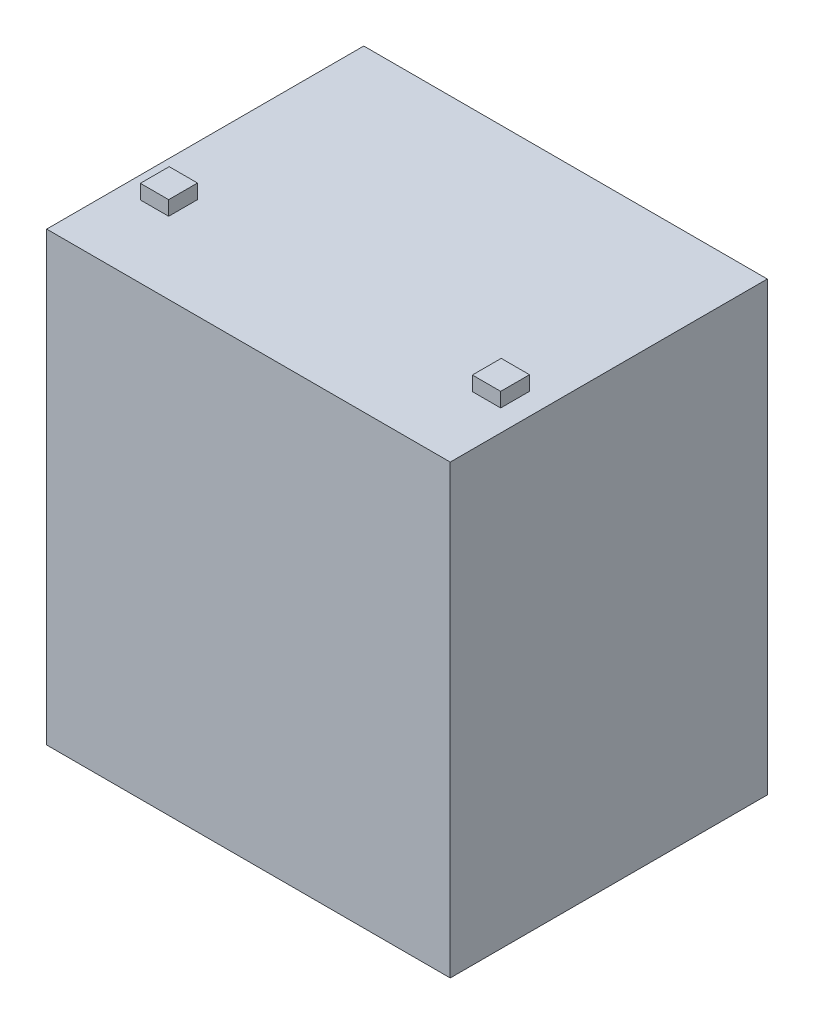
SolidWorks part; units mm, degrees
ref_plane "Front Plane" through (0, 0, 0) normal (0, 0, 1) x (1, 0, 0)
ref_plane "Top Plane" through (0, 0, 0) normal (0, 1, 0) x (1, 0, 0)
ref_plane "Right Plane" through (0, 0, 0) normal (1, 0, 0) x (0, 0, -1)
sketch "Sketch2" plane through (0, 0, 0) normal (0, 0, 1) x (1, 0, 0)
  line L1 (-44.45, -49.2125) -> (44.45, -49.2125)
  line L2 (-44.45, -49.2125) -> (-44.45, 49.2125)
  line L3 (-44.45, 49.2125) -> (44.45, 49.2125)
  line L4 (44.45, -49.2125) -> (44.45, 49.2125)
  line L5 (-44.45, -49.2125) -> (44.45, 49.2125) construction
  line L6 (-44.45, 49.2125) -> (44.45, -49.2125) construction
  point P0 (0, 0)
  dimension "D1" = 88.9
  dimension "D2" = 98.425
extrude "Boss-Extrude1" add sketch "Sketch2" against normal blind 69.85
sketch "Sketch3" plane through (0, 49.2125, 0) normal (0, 1, 0) x (1, 0, 0)
  line L0 (44.45, 0) -> (-44.45, 0) construction
  line L1 (-39.6875, 15.875) -> (-33.4517, 15.875)
  line L2 (-39.6875, 15.875) -> (-39.6875, 22.225)
  line L3 (-39.6875, 22.225) -> (-33.4517, 22.225)
  line L4 (-33.4517, 15.875) -> (-33.4517, 22.225)
  line L5 (39.6875, 15.875) -> (33.4517, 15.875)
  line L6 (33.4517, 15.875) -> (33.4517, 22.225)
  line L7 (39.6875, 15.875) -> (39.6875, 22.225)
  line L8 (39.6875, 22.225) -> (33.4517, 22.225)
  line L9 (-44.45, 69.85) -> (-44.45, 0) construction
  line L10 (0, 0) -> (0, 69.85) construction
  line L11 (44.45, 69.85) -> (-44.45, 69.85) construction
  dimension "D1" = 6.35
  dimension "D2" = 6.2358
  dimension "D3" = 15.875
  dimension "D4" = 4.7625
extrude "Boss-Extrude2" add sketch "Sketch3" along normal blind 3.175
